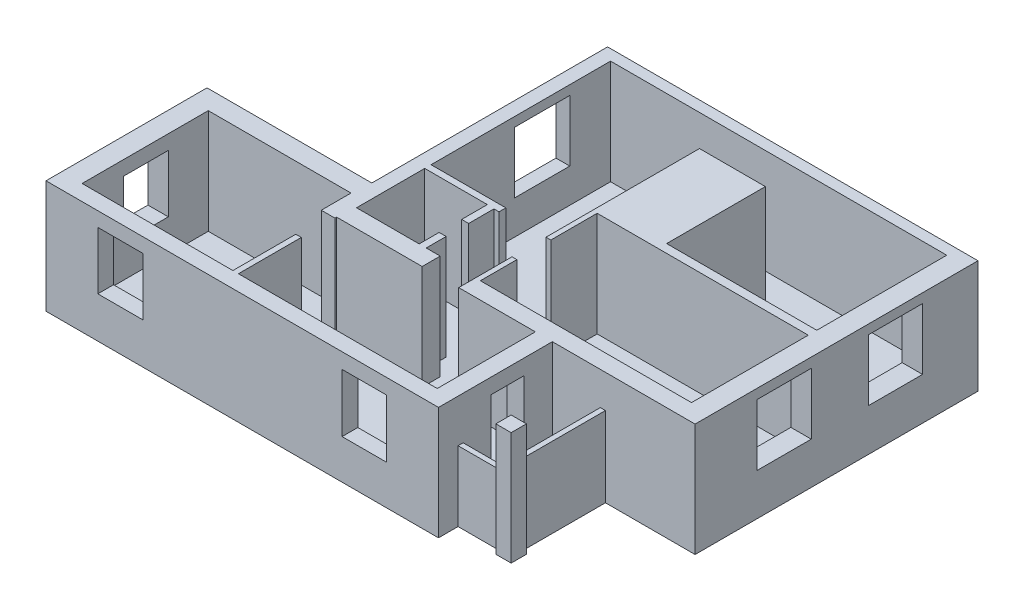
SolidWorks part; units mm, degrees
ref_plane "Спереди" through (0, 0, 0) normal (0, 0, 1) x (1, 0, 0)
ref_plane "Сверху" through (0, 0, 0) normal (0, 1, 0) x (1, 0, 0)
ref_plane "Справа" through (0, 0, 0) normal (1, 0, 0) x (0, 0, -1)
sketch "Эскиз1" plane through (0, 0, 0) normal (0, 1, 0) x (1, 0, 0)
  line L0 (0, 0) -> (7823.2617, 0)
  line L1 (3000, -735.9756) -> (2830, -735.9756)
  line L2 (2830, -735.9756) -> (2830, -4350)
  line L3 (0, 0) -> (0, -4225)
  line L4 (0, -4225) -> (1760, -4225)
  line L5 (4380, -735.9756) -> (4230, -735.9756)
  line L6 (4230, -735.9756) -> (4230, -1709.6351) construction
  line L7 (4380, -735.9756) -> (4380, -3060)
  line L8 (4380, -3060) -> (7915, -3060)
  line L9 (7915, -3060) -> (7915, 0)
  line L10 (7915, 0) -> (7823.2617, 0)
  line L11 (1760, -4225) -> (1760, -4385)
  line L12 (1760, -4385) -> (1640, -4385)
  line L13 (1640, -4385) -> (1640, -4980)
  line L14 (1640, -4980) -> (1475, -4980)
  line L15 (1475, -4980) -> (1475, -4375)
  line L16 (1475, -4375) -> (0, -4375)
  line L17 (0, -4375) -> (0, -5980)
  line L18 (0, -5980) -> (1475, -5980)
  line L19 (1475, -5980) -> (1475, -5510)
  line L20 (1475, -5510) -> (1640, -5510)
  line L21 (1640, -5510) -> (1640, -5980)
  line L22 (1640, -5980) -> (1970, -5980)
  line L23 (1970, -5980) -> (1970, -6405)
  line L24 (6045, -8625) -> (6045, -8745)
  line L25 (1970, -6405) -> (-45, -6405)
  line L26 (2830, -4350) -> (2945, -4350)
  line L27 (2945, -4350) -> (2945, -3260)
  line L28 (2945, -5150) -> (2830, -5150)
  line L29 (2830, -5150) -> (2830, -6010)
  line L30 (2945, -3260) -> (7915, -3260)
  line L31 (2830, -6010) -> (2830, -6405)
  line L32 (2830, -6405) -> (4635, -6405)
  line L33 (7915, -3260) -> (7915, -6010)
  line L34 (7915, -6010) -> (2945, -6010)
  line L35 (2945, -6010) -> (2945, -5150)
  line L36 (4635, -6405) -> (4635, -7075)
  line L37 (4635, -7075) -> (5035, -7075)
  line L38 (5035, -7855) -> (4635, -7855)
  line L39 (4635, -7855) -> (4635, -8715)
  line L40 (4635, -8715) -> (-45, -8715)
  line L41 (-45, -8715) -> (-45, -7235)
  line L42 (-45, -7235) -> (-175, -7235)
  line L43 (-175, -7235) -> (-175, -8715)
  line L44 (-175, -8715) -> (-3725, -8715)
  line L45 (-3725, -8715) -> (-3725, -5745)
  line L46 (-3725, -5745) -> (-365, -5745)
  line L47 (-365, -5745) -> (-365, -6445)
  line L48 (-365, -6445) -> (-45, -6445)
  line L49 (-45, -6445) -> (-45, -6405)
  line L50 (-365, -6305) -> (-175, -6305) construction
  line L51 (-175, -6305) -> (-175, -6445) construction
  line L52 (-4205.7925, -6685) -> (-4205.7925, -7740) construction
  line L53 (-2985, -9014.0938) -> (-1925, -9014.0938) construction
  line L54 (-268.0986, -960) -> (-268.0986, -2260) construction
  line L55 (2765, -9359.9129) -> (3815, -9359.9129) construction
  line L56 (5035, -7075) -> (5035, -6405)
  line L57 (5035, -6405) -> (6165, -6405)
  line L58 (6165, -6405) -> (6165, -8385)
  line L59 (6045, -8505) -> (5035, -8505)
  line L60 (5035, -8505) -> (5035, -7855)
  line L61 (5035, -8625) -> (6045, -8625)
  line L62 (5035, -8625) -> (5035, -9085)
  line L63 (5035, -9085) -> (-4205, -9085)
  line L64 (6285, -8385) -> (6285, -6405)
  line L65 (8239.056, -3670) -> (8239.056, -4950) construction
  line L66 (8208.6733, -1050) -> (8208.6733, -2320) construction
  line L67 (-325, 255) -> (-325, -5295)
  line L68 (6045, -8385) -> (6165, -8385)
  line L69 (6045, -8385) -> (6045, -8505)
  line L70 (6045, -8745) -> (6405, -8745)
  line L71 (6405, -8385) -> (6405, -8745)
  line L72 (-325, -5295) -> (-4205, -5295)
  line L73 (-4205, -5295) -> (-4205, -9085)
  line L74 (6285, -6405) -> (8395, -6405)
  line L75 (8395, -6405) -> (8395, 255)
  line L76 (8395, 255) -> (-325, 255)
  line L77 (7915, -6010) -> (8395, -6010) construction
  line L78 (-3725, -5745) -> (-4205, -5745) construction
  line L81 (6285, -8385) -> (6405, -8385)
  line L82 (3000, -735.9756) -> (4230, -735.9756)
  dimension "D1" = 7915
  dimension "D2" = 2830
  dimension "D3" = 170
  dimension "D4" = 150
  dimension "D5" = 4230
  dimension "D6" = 4225
  dimension "D7" = 3060
  dimension "D8" = 1760
  dimension "D9" = 120
  dimension "D10" = 160
  dimension "D11" = 530
  dimension "D12" = 470
  dimension "D13" = 9340
  dimension "D14" = 425
  dimension "D15" = 1475
  dimension "D16" = 150
  dimension "D17" = 5980
  dimension "D18" = 4350
  dimension "D19" = 5150
  dimension "D20" = 860
  dimension "D21" = 2750
  dimension "D22" = 4970
  dimension "D23" = 1090
  dimension "D24" = 40
  dimension "D25" = 830
  dimension "D26" = 2310
  dimension "D27" = 2015
  dimension "D28" = 4680
  dimension "D29" = 860
  dimension "D30" = 1640
  dimension "D31" = 3680
  dimension "D32" = 2970
  dimension "D33" = 130
  dimension "D34" = 3360
  dimension "D35" = 560
  dimension "D36" = 1130
  dimension "D37" = 400
  dimension "D38" = 2100
  dimension "D39" = 2220
  dimension "D40" = 120
  dimension "D41" = 370
  dimension "D42" = 740
  dimension "D43" = 1800
  dimension "D44" = 820
  dimension "D45" = 1870
  dimension "D46" = 975
  dimension "D47" = 2030
  dimension "D48" = 960
  dimension "D49" = 2260
  dimension "D50" = 1050
  dimension "D51" = 2320
  dimension "D52" = 410
  dimension "D53" = 1690
  dimension "D54" = 360
  dimension "D55" = 12600
  dimension "D56" = 5550
  dimension "D57" = 120
  dimension "D58" = 8720
  dimension "D59" = 3360
extrude "Бобышка-Вытянуть1" add sketch "Эскиз1" along normal blind 2460
sketch "Эскиз2" plane through (0, 0, 0) normal (0, -1, 0) x (1, 0, 0)
  line L0 (-4205, 5295) -> (-4205, 9085) construction
  line L1 (-4205, 5295) -> (-4205, 9085)
  line L2 (-4205, 9085) -> (5035, 9085) construction
  line L3 (-4205, 9085) -> (5035, 9085)
  line L4 (-325, 5295) -> (-4205, 5295) construction
  line L5 (-325, 5295) -> (-4205, 5295)
  line L6 (-325, -255) -> (-325, 5295) construction
  line L7 (-325, -255) -> (-325, 5295)
  line L8 (8395, -255) -> (-325, -255) construction
  line L9 (8395, -255) -> (-325, -255)
  line L10 (8395, 6405) -> (8395, -255) construction
  line L11 (8395, 6405) -> (8395, -255)
  line L12 (6285, 6405) -> (8395, 6405) construction
  line L13 (6285, 6405) -> (8395, 6405)
  line L14 (6045, 8745) -> (6405, 8745) construction
  line L15 (6045, 8745) -> (6405, 8745)
  line L16 (5035, 8625) -> (6045, 8625) construction
  line L17 (5035, 8625) -> (6045, 8625)
  line L18 (5035, 9085) -> (5035, 8625) construction
  line L19 (5035, 9085) -> (5035, 8625)
  line L20 (6405, 8385) -> (6285, 8385) construction
  line L21 (6405, 8385) -> (6285, 8385)
  line L22 (6405, 8745) -> (6405, 8385) construction
  line L23 (6405, 8745) -> (6405, 8385)
  line L24 (6285, 8385) -> (6285, 6405) construction
  line L25 (6285, 8385) -> (6285, 6405)
  line L26 (6045, 8625) -> (6045, 8745) construction
  line L27 (6045, 8625) -> (6045, 8745)
extrude "Бобышка-Вытянуть2" add sketch "Эскиз2" along normal blind 200
sketch "Эскиз3" plane through (0, 0, 8625) normal (0, 0, 1) x (1, 0, 0)
  line L0 (5035, 2460) -> (5035, -200) construction
  line L1 (5035, 2460) -> (5035, 1448.742)
  line L2 (6045, 2460) -> (6045, -200) construction
  line L3 (6045, 2460) -> (6045, 1448.742)
  line L4 (5035, 1448.742) -> (6045, 1448.742)
  line L5 (5035, 2460) -> (6045, 2460)
extrude "Вырез-Вытянуть1" cut sketch "Эскиз3" against normal up to next
sketch "Эскиз4" plane through (6285, 0, 0) normal (1, 0, 0) x (0, 0, -1)
  line L0 (-6405, 2460) -> (-6405, -200) construction
  line L1 (-6405, 2460) -> (-6405, 1681.1266)
  line L2 (-8385, 2460) -> (-8385, -200) construction
  line L3 (-8385, 2460) -> (-8385, 1681.1266)
  line L4 (-8385, 2460) -> (-6405, 2460) construction
  line L5 (-8385, 2460) -> (-6405, 2460)
  line L6 (-8385, 1681.1266) -> (-6405, 1681.1266)
extrude "Вырез-Вытянуть2" cut sketch "Эскиз4" against normal up to next
sketch "Эскиз5" plane through (5035, 0, 0) normal (1, 0, 0) x (0, 0, -1)
  line L0 (-7855, 2460) -> (-7855, 0) construction
  line L1 (-7075, 2460) -> (-7855, 2460)
  line L2 (-7075, 2460) -> (-7075, 2100)
  line L3 (-7075, 2100) -> (-7855, 2100)
  line L4 (-7855, 2460) -> (-7855, 2100)
  line L5 (-6405, 0) -> (-7075, 0) construction
  dimension "D1" = 2100
extrude "Бобышка-Вытянуть3" add sketch "Эскиз5" against normal up to surface (400 mm away) up to face at (4635, 1230, 6740)
sketch "Эскиз6" plane through (0, 0, 9085) normal (0, 0, 1) x (1, 0, 0)
  line L0 (4635, 2460) -> (4635, 0) construction
  line L1 (3815, 730) -> (2765, 730)
  line L2 (3815, 730) -> (3815, 2100)
  line L3 (3815, 2100) -> (2765, 2100)
  line L4 (2765, 730) -> (2765, 2100)
  line L5 (-45, 0) -> (4635, 0) construction
  line L6 (-3725, 2460) -> (-3725, 0) construction
  line L7 (-2985, 765) -> (-1925, 765)
  line L8 (-2985, 765) -> (-2985, 2120)
  line L9 (-2985, 2120) -> (-1925, 2120)
  line L10 (-1925, 765) -> (-1925, 2120)
  line L11 (-365, 0) -> (-3725, 0) construction
  dimension "D1" = 820
  dimension "D2" = 1050
  dimension "D3" = 1370
  dimension "D4" = 730
  dimension "D5" = 740
  dimension "D6" = 1060
  dimension "D7" = 765
  dimension "D8" = 1355
extrude "Вырез-Вытянуть3" cut sketch "Эскиз6" against normal up to next
sketch "Эскиз7" plane through (-4205, 0, 0) normal (-1, 0, 0) x (0, 0, 1)
  line L0 (6445, 0) -> (5745, 0) construction
  line L1 (6685, 765) -> (7740, 765)
  line L2 (6685, 765) -> (6685, 2120)
  line L3 (6685, 2120) -> (7740, 2120)
  line L4 (7740, 765) -> (7740, 2120)
  line L5 (8715, 2460) -> (8715, 0) construction
  dimension "D1" = 1355
  dimension "D2" = 765
  dimension "D3" = 975
  dimension "D4" = 1055
extrude "Вырез-Вытянуть4" cut sketch "Эскиз7" against normal up to next
sketch "Эскиз8" plane through (-325, 0, 0) normal (-1, 0, 0) x (0, 0, 1)
  line L0 (0, 2460) -> (0, 0) construction
  line L1 (960, 2240) -> (2260, 2240)
  line L2 (960, 2240) -> (960, 800)
  line L3 (960, 800) -> (2260, 800)
  line L4 (2260, 2240) -> (2260, 800)
  line L5 (0, 0) -> (4225, 0) construction
  dimension "D1" = 960
  dimension "D2" = 1300
  dimension "D3" = 800
  dimension "D4" = 1440
extrude "Вырез-Вытянуть5" cut sketch "Эскиз8" against normal up to next
sketch "Эскиз9" plane through (8395, 0, 0) normal (1, 0, 0) x (0, 0, -1)
  line L0 (-5150, 0) -> (-6010, 0) construction
  line L1 (-4950, 785) -> (-3670, 785)
  line L2 (-4950, 785) -> (-4950, 2230)
  line L3 (-4950, 2230) -> (-3670, 2230)
  line L4 (-3670, 785) -> (-3670, 2230)
  line L5 (-2320, 795) -> (-1050, 795)
  line L6 (-2320, 795) -> (-2320, 2240)
  line L7 (-2320, 2240) -> (-1050, 2240)
  line L8 (-1050, 795) -> (-1050, 2240)
  line L9 (-735.9756, 0) -> (-3060, 0) construction
  line L10 (-3260, 2460) -> (-3260, 0) construction
  line L11 (0, 2460) -> (0, 0) construction
  dimension "D1" = 785
  dimension "D2" = 1445
  dimension "D3" = 795
  dimension "D4" = 1445
  dimension "D5" = 410
  dimension "D6" = 1690
  dimension "D7" = 1050
  dimension "D8" = 1270
extrude "Вырез-Вытянуть6" cut sketch "Эскиз9" against normal up to next
